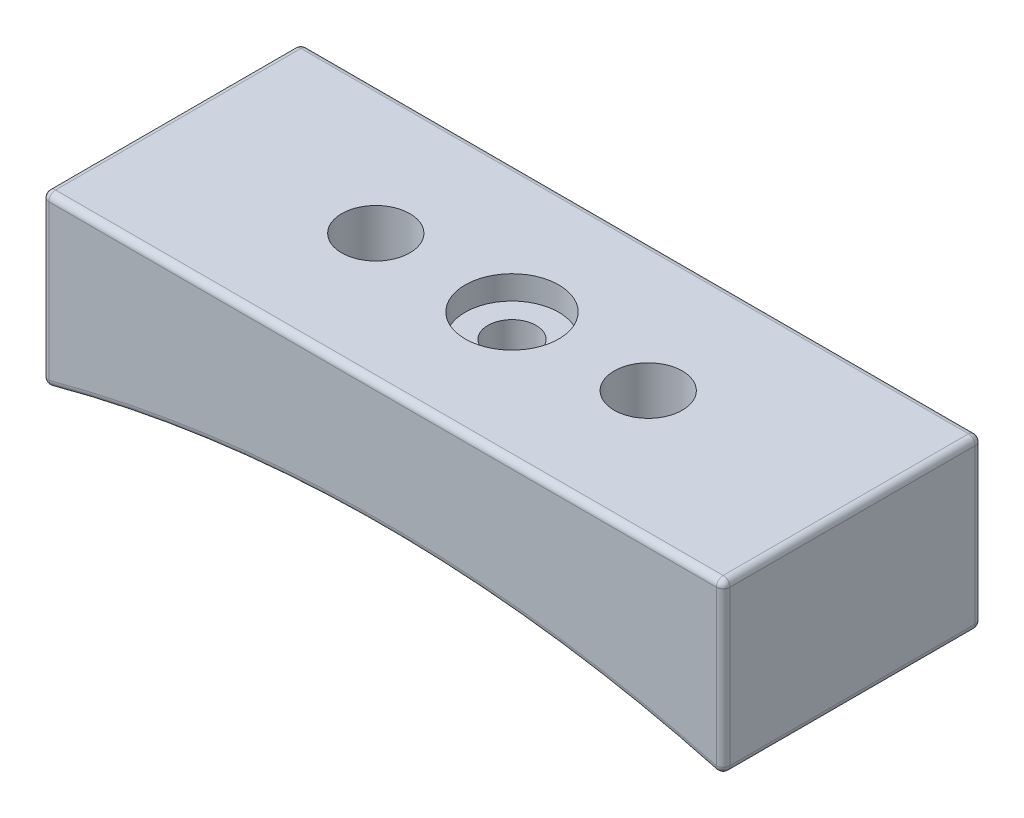
SolidWorks part; units mm, degrees
ref_plane "Front Plane" through (0, 0, 0) normal (0, 0, 1) x (1, 0, 0)
ref_plane "Top Plane" through (0, 0, 0) normal (0, 1, 0) x (1, 0, 0)
ref_plane "Right Plane" through (0, 0, 0) normal (1, 0, 0) x (0, 0, -1)
sketch "Sketch1" plane through (0, 0, 0) normal (0, 0, 1) x (1, 0, 0)
  line L0 (0, 0) -> (0, 21.7025) construction
  line L1 (-31.75, 12.7) -> (31.75, 12.7)
  line L2 (-31.75, 12.7) -> (-31.75, -3.175)
  line L4 (31.75, 12.7) -> (31.75, -3.175)
  line L5 (-31.75, 12.7) -> (31.75, -3.175) construction
  line L6 (-31.75, -3.175) -> (31.75, 12.7) construction
  arc A0 (-31.75, -3.175) -> (31.75, -3.175) centre (0, -117.0694) cw
  point P0 (0, 4.7625)
  point P9 (0, 12.7)
  point P10 (0, 17.0011)
  dimension "D3" = 118.237
  dimension "D1" = 63.5
  dimension "D2" = 15.875
extrude "Boss-Extrude1" add sketch "Sketch1" along normal blind 24.13
hole_wizard "CBORE for #8 Button Head Cap Screw1" positions "Sketch2" profile "Sketch3" counterbore size "#8" standard "ANSI Inch" end condition through all
sketch "Sketch2" plane through (0, 12.7, 0) normal (0, 1, 0) x (1, 0, 0)
  line L0 (-31.75, 0) -> (31.75, -24.13) construction
  point P6 (0, -12.065)
sketch "Sketch3" plane through (0, 12.7, 12.065) normal (1, 0, 0) x (0, 0, 1)
  line L0 (0, 0) -> (0, 15.875)
  line L1 (0, 15.875) -> (2.2479, 15.875)
  line L3 (2.2479, 15.875) -> (2.2479, 2.2098)
  line L4 (2.2479, 2.2098) -> (4.3663, 2.2098)
  line L5 (4.3663, 2.2098) -> (4.3663, 0)
  line L7 (4.3663, 0) -> (0, 0)
  line L11 (0, -6.35) -> (0, 107.95) construction
  dimension "Thru Hole Dia." = 4.4958
  dimension "Thru Hole Depth" = 15.875
  dimension "C'Bore Dia." = 8.7325
  dimension "C'Bore Depth" = 2.2098
ref_plane "Plane2" through (0, 0, 0) normal (1, 0, 0) x (0, 0, -1)
ref_plane "Plane4" through (0, 0, 12.065) normal (0, 0, -1) x (-1, 0, 0)
ref_plane "Plane5" through (0, 1.1676, 0) normal (0, -1, 0) x (-1, 0, 0)
sketch "Sketch6" plane through (0, 1.1676, 0) normal (0, -1, 0) x (-1, 0, 0)
  line L0 (7.9238, -12.065) -> (-7.9238, -12.065) construction
  line L1 (0, 7.9238) -> (0, -7.9238) construction
  line L2 (0, -12.065) -> (0, -37.3295) construction
  circle A0 centre (12.7, -12.065) radius 3.175
  circle A1 centre (-12.7, -12.065) radius 3.175
  dimension "D1" = 6.35
  dimension "D2" = 12.7
extrude "Cut-Extrude1" cut sketch "Sketch6" against normal through all both and the other way through all
sketch "Sketch7" plane through (0, 1.1676, 0) normal (0, -1, 0) x (-1, 0, 0)
  line L0 (0, -12.065) -> (0, -35.0411) construction
  circle A0 centre (12.7, -12.065) radius 8.128
  circle A1 centre (-12.7, -12.065) radius 8.128
  dimension "D1" = 16.256
extrude "Cut-Extrude2" cut sketch "Sketch7" against normal blind 5.588 and the other way through all
fillet "Fillet1" radius 0.635 12 edges at (0, 12.7, 0) (0, 1.1676, 0) (-31.75, 12.7, 12.065) (-31.75, -3.175, 12.065) (-31.75, 4.7625, 0) (-31.75, 4.7625, 24.13) (0, 12.7, 24.13) (0, 1.1676, 24.13) (31.75, -3.175, 12.065) (31.75, 4.7625, 24.13) (31.75, 12.7, 12.065) (31.75, 4.7625, 0)
